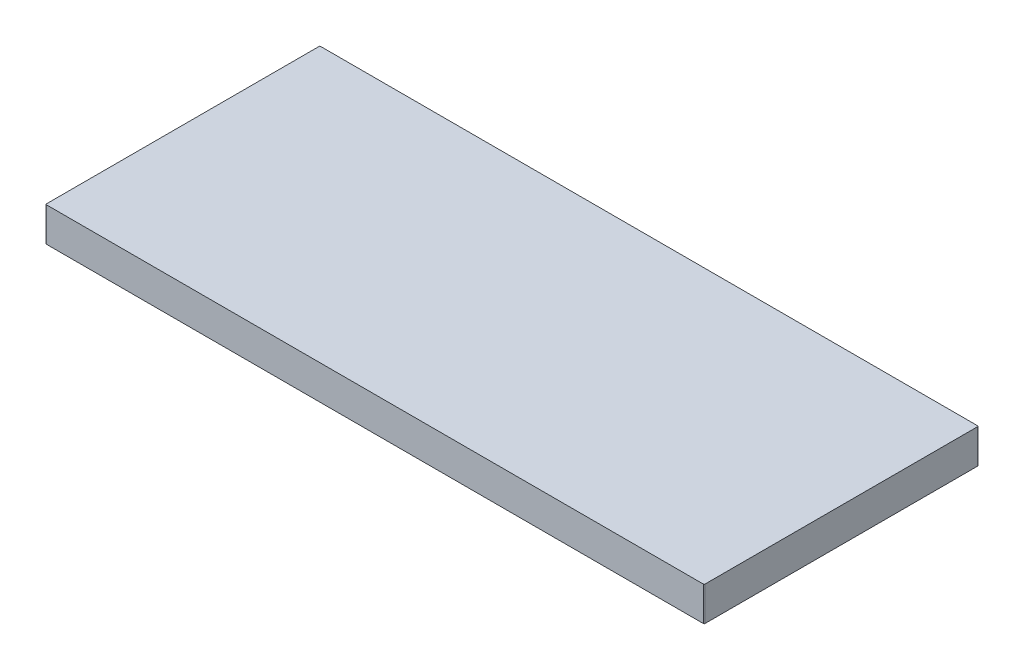
SolidWorks part; units mm, degrees
ref_plane "Front Plane" through (0, 0, 0) normal (0, 0, 1) x (1, 0, 0)
ref_plane "Top Plane" through (0, 0, 0) normal (0, 1, 0) x (1, 0, 0)
ref_plane "Right Plane" through (0, 0, 0) normal (1, 0, 0) x (0, 0, -1)
sketch "Sketch1" plane through (0, 0, 0) normal (0, 1, 0) x (1, 0, 0)
  line L4 (48.15, -19.95) -> (48.15, 19.95)
  line L5 (48.05, 20.05) -> (-48.05, 20.05)
  line L6 (-48.15, 19.95) -> (-48.15, -19.95)
  line L7 (-48.05, -20.05) -> (48.05, -20.05)
  line L8 (48.15, -19.95) -> (48.15, 19.95)
  line L9 (48.05, 20.05) -> (-48.05, 20.05)
  line L10 (-48.15, 19.95) -> (-48.15, -19.95)
  line L11 (-48.05, -20.05) -> (48.05, -20.05)
  arc A4 (48.15, 19.95) -> (48.05, 20.05) centre (48.05, 19.95) ccw
  arc A5 (-48.05, 20.05) -> (-48.15, 19.95) centre (-48.05, 19.95) ccw
  arc A6 (-48.15, -19.95) -> (-48.05, -20.05) centre (-48.05, -19.95) ccw
  arc A7 (48.05, -20.05) -> (48.15, -19.95) centre (48.05, -19.95) ccw
  arc A8 (48.15, 19.95) -> (48.05, 20.05) centre (48.05, 19.95) ccw
  arc A9 (-48.05, 20.05) -> (-48.15, 19.95) centre (-48.05, 19.95) ccw
  arc A10 (-48.15, -19.95) -> (-48.05, -20.05) centre (-48.05, -19.95) ccw
  arc A11 (48.05, -20.05) -> (48.15, -19.95) centre (48.05, -19.95) ccw
  dimension "D1" = 0
extrude "Boss-Extrude1" add sketch "Sketch1" along normal blind 5
